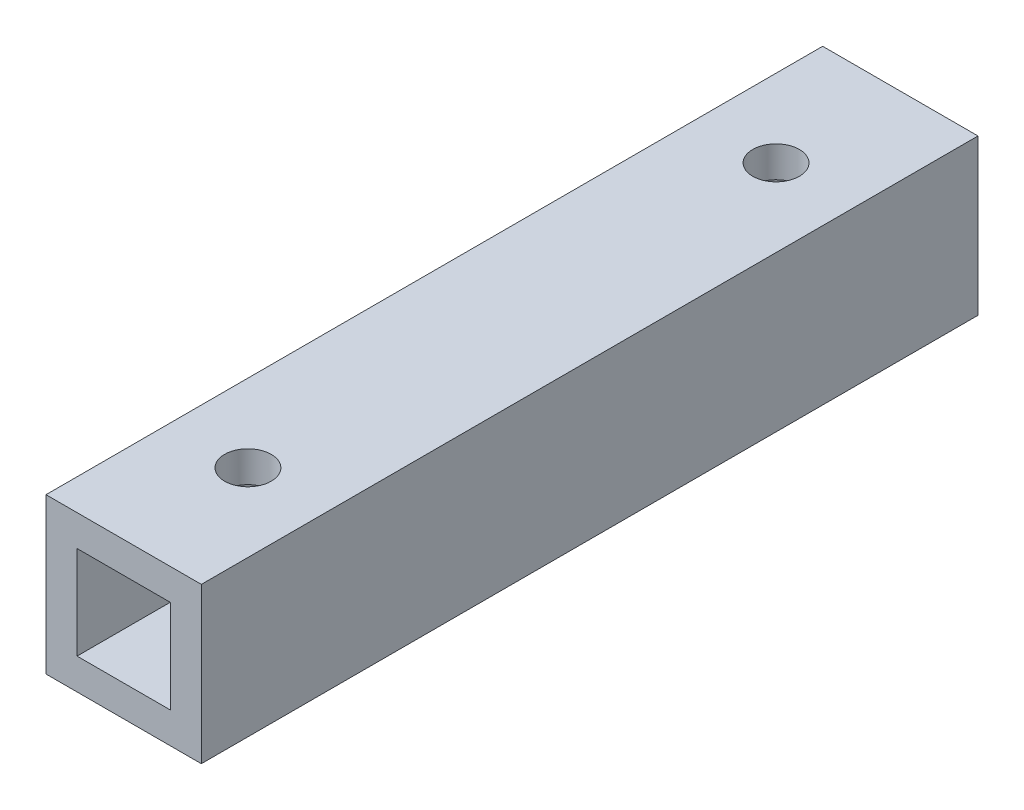
SolidWorks part; units mm, degrees
ref_plane "前视基准面" through (0, 0, 0) normal (0, 0, 1) x (1, 0, 0)
ref_plane "上视基准面" through (0, 0, 0) normal (0, 1, 0) x (1, 0, 0)
ref_plane "右视基准面" through (0, 0, 0) normal (1, 0, 0) x (0, 0, -1)
sketch "草图2" plane through (0, 0, 0) normal (0, 0, 1) x (1, 0, 0)
  line L1 (-5, 5) -> (5, 5)
  line L2 (-5, 5) -> (-5, -5)
  line L3 (-5, -5) -> (5, -5)
  line L4 (5, 5) -> (5, -5)
  line L5 (-5, 5) -> (5, -5) construction
  line L6 (-5, -5) -> (5, 5) construction
  point P0 (0, 0)
  dimension "D1" = 10
  dimension "D2" = 10
extrude "凸台-拉伸1" add sketch "草图2" along normal mid plane 50
sketch "草图3" plane through (0, 5, 0) normal (0, 1, 0) x (1, 0, 0)
  line L0 (5, 25) -> (-5, 25) construction
  line L1 (0, 25) -> (0, 45.5987) construction
  circle A0 centre (0, 17) radius 1.5
  dimension "D1" = 8
  dimension "D2" = 3
extrude "切除-拉伸1" cut sketch "草图3" against normal through all both
mirror "镜向1" about plane through (0, 0, 0) normal (0, 0, 1) of "切除-拉伸1"
sketch "草图4" plane through (0, 0, 25) normal (0, 0, 1) x (1, 0, 0)
  line L1 (-3, 3) -> (3, 3)
  line L2 (-3, 3) -> (-3, -3)
  line L3 (-3, -3) -> (3, -3)
  line L4 (3, 3) -> (3, -3)
  line L5 (-3, 3) -> (3, -3) construction
  line L6 (-3, -3) -> (3, 3) construction
  point P0 (0, 0)
  dimension "D1" = 6
  dimension "D2" = 6
extrude "切除-拉伸2" cut sketch "草图4" against normal through all both
